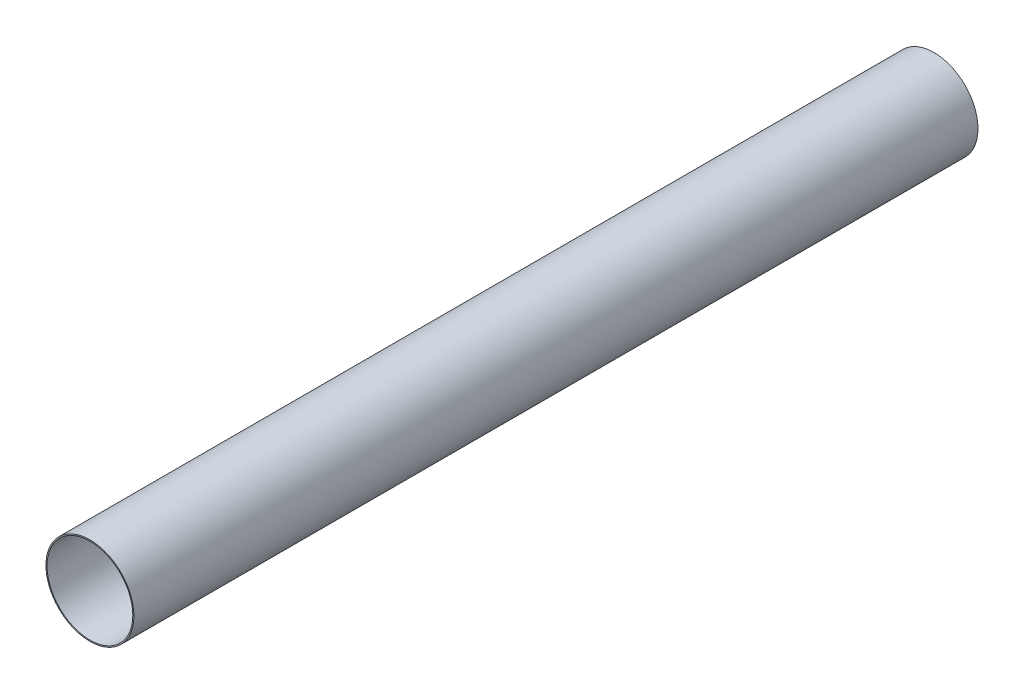
SolidWorks part; units mm, degrees
material "E-Glass Fiber"
ref_plane "Front" through (0, 0, 0) normal (0, 0, 1) x (1, 0, 0)
ref_plane "Top" through (0, 0, 0) normal (0, 1, 0) x (1, 0, 0)
ref_plane "Right" through (0, 0, 0) normal (1, 0, 0) x (0, 0, -1)
sketch "Sketch1" plane through (0, 0, 0) normal (0, 0, 1) x (1, 0, 0)
  circle A0 centre (0, 0) radius 78.2
  circle A1 centre (0, 0) radius 76.2
  dimension "D1" = 156.4
  dimension "D2" = 152.4
extrude "Boss-Extrude1" add sketch "Sketch1" along normal blind 1500
